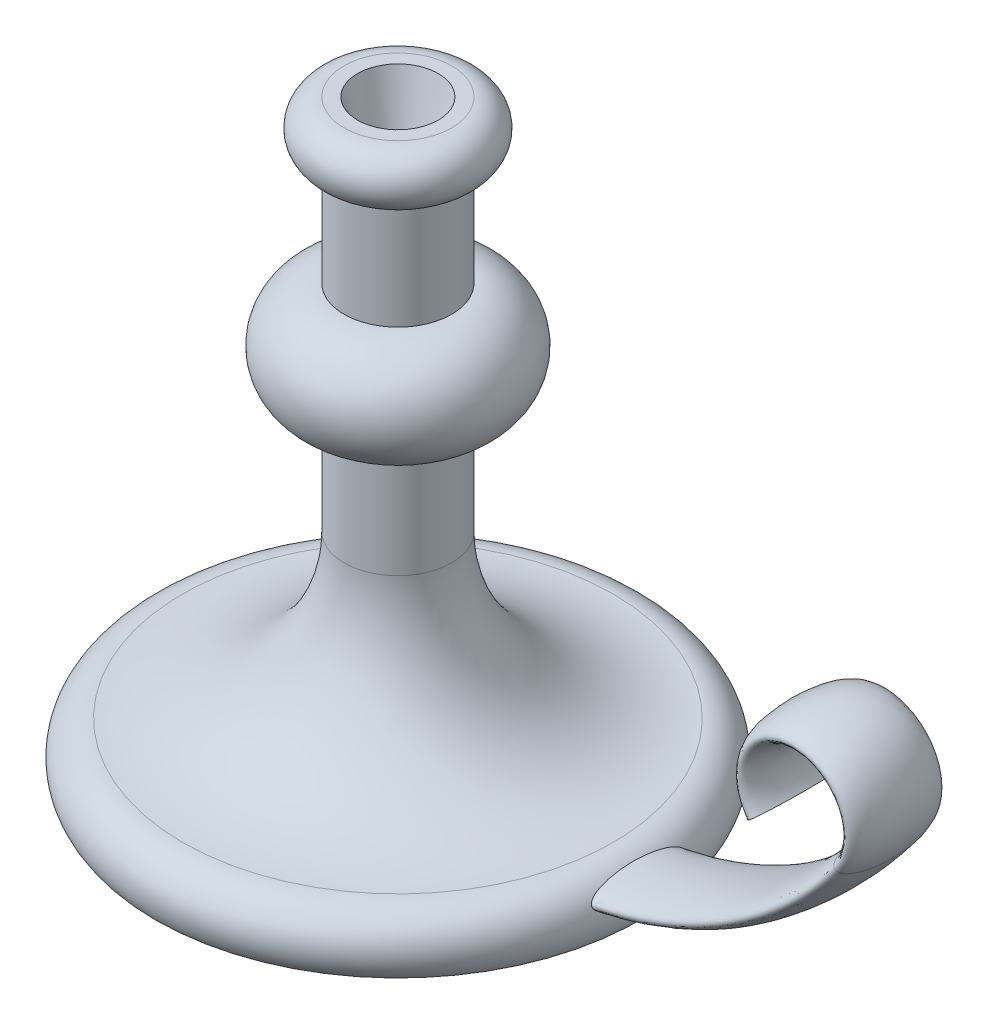
SolidWorks part; units mm, degrees
ref_plane "Płaszczyzna przednia" through (0, 0, 0) normal (0, 0, 1) x (1, 0, 0)
ref_plane "Płaszczyzna górna" through (0, 0, 0) normal (0, 1, 0) x (1, 0, 0)
ref_plane "Płaszczyzna prawa" through (0, 0, 0) normal (1, 0, 0) x (0, 0, -1)
sketch "Szkic2" plane through (0, 0, 0) normal (0, 0, 1) x (1, 0, 0)
  line L0 (0, 0) -> (0, 220)
  line L1 (0, 220) -> (20, 220)
  line L3 (20, 120) -> (20, 80)
  line L4 (90, 0) -> (0, 0)
  line L6 (20, 200) -> (20, 160)
  arc A0 (20, 220) -> (20, 200) centre (20, 210) cw
  arc A1 (20, 160) -> (20, 120) centre (20, 140) cw
  arc A2 (20, 80) -> (80, 20) centre (80, 80) ccw
  arc A3 (80, 20) -> (90, 0) centre (80, 7.5) cw
  point P13 (0, 0)
  point P14 (-184.653, 15.7122)
  point P15 (0, 0)
  point P16 (-190.4576, 24.0564)
  point P17 (0, 0)
  point P18 (0, 0)
  point P19 (-190.4576, 38.9308)
  point P20 (20, 200)
  point P21 (0, 0)
  dimension "D4" = 20
  dimension "D8" = 10
  dimension "D9" = 60
  dimension "D10" = 12.5
  dimension "D3" = 40
  dimension "D5" = 220
  dimension "D6" = 90
  dimension "D7" = 20
  dimension "D11" = 80
revolve "Obrót1" add sketch "Szkic2" angle 360 about L0
sketch "Szkic3" plane through (0, 0, 0) normal (0, 0, 1) x (1, 0, 0)
  line L0 (0, 10) -> (60, 10)
  arc A0 (60, 10) -> (180, 70) centre (60, 160) ccw
  arc A1 (180, 70) -> (148, 70) centre (164, 82) ccw
  point P6 (-210.4576, -112.4129)
  point P7 (-53.8797, -55.8642)
  point P8 (-210.4576, -111.4191)
  point P9 (-209.143, -111.177)
  point P10 (-210.4576, -110.846)
  point P11 (0, 0)
  point P12 (0, 0)
  point P13 (-210.4576, -112.1485)
  point P14 (0, 13.5003)
  point P15 (0, 0)
  dimension "D2" = 150
  dimension "D4" = 20
  dimension "D1" = 60
  dimension "D3" = 60
  dimension "D5" = 10
sketch "Szkic5" plane through (0, 0, 0) normal (1, 0, 0) x (0, 0, -1)
  ellipse E0 centre (0, 10) end of major axis (17.5, 10) minor radius 5
  point P1 (-85.7151, 134.1723)
  point P7 (-157.787, 141.2905)
  point P8 (0, 0)
  point P9 (0, 0)
  point P10 (-157.1938, 142.4768)
  point P11 (0, 0)
  point P12 (0, 0)
  point P13 (0, 10)
  dimension "D1" = 35
  dimension "D2" = 10
sweep "Wyciągnięcie po ścieżce1" add profiles "Szkic5" path "Szkic3"
sketch "Szkic8" plane through (0, 220, 0) normal (0, 1, 0) x (1, 0, 0)
  circle A0 centre (0, 0) radius 15
  dimension "D1" = 30
extrude "Wytnij-wyciągnięcie1" cut sketch "Szkic8" against normal blind 25 draft 15
